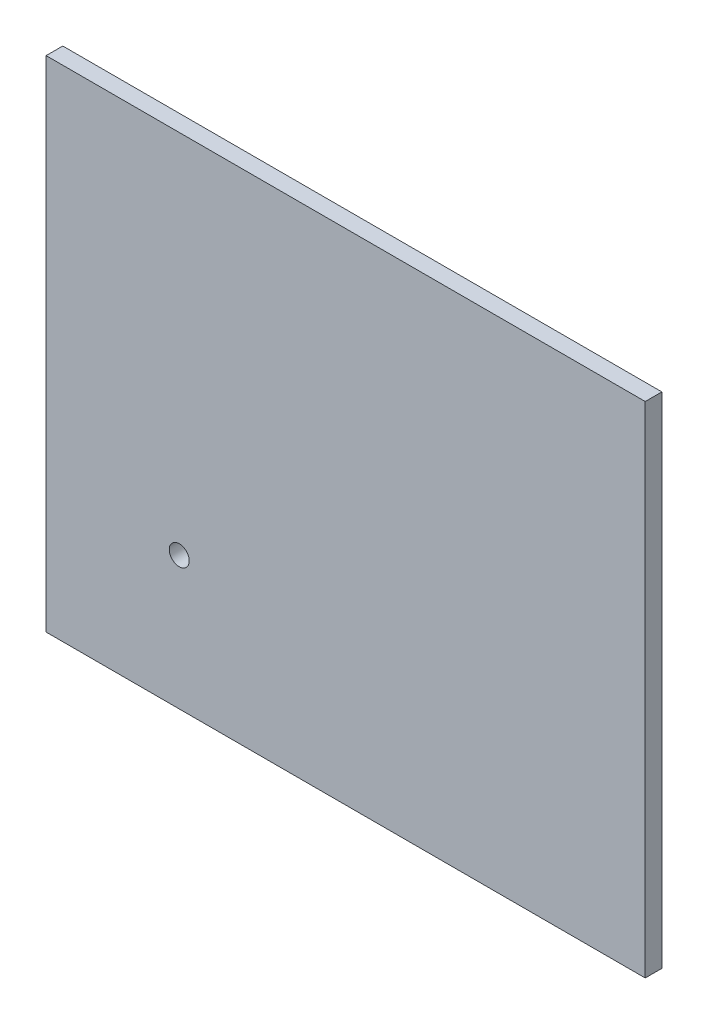
SolidWorks part; units mm, degrees
ref_plane "Front Plane" through (0, 0, 0) normal (0, 0, 1) x (1, 0, 0)
ref_plane "Top Plane" through (0, 0, 0) normal (0, 1, 0) x (1, 0, 0)
ref_plane "Right Plane" through (0, 0, 0) normal (1, 0, 0) x (0, 0, -1)
sketch "Sketch1" plane through (0, 0, 0) normal (0, 0, 1) x (1, 0, 0)
  line L0 (-119.0922, -35) -> (145.4611, -35) construction
  line L1 (90, -75) -> (-90, -75)
  line L2 (90, -75) -> (90, 75)
  line L3 (90, 75) -> (-90, 75)
  line L4 (-90, -75) -> (-90, 75)
  line L5 (90, -75) -> (-90, 75) construction
  line L6 (90, 75) -> (-90, -75) construction
  line L7 (-50, -0.7349) -> (-50, -137.6801) construction
  circle A0 centre (-50, -35) radius 3
  point P0 (0, 0)
  dimension "D5" = 6
  dimension "D1" = 180
  dimension "D2" = 150
  dimension "D3" = 40
  dimension "D4" = 40
extrude "Boss-Extrude1" add sketch "Sketch1" along normal blind 5
